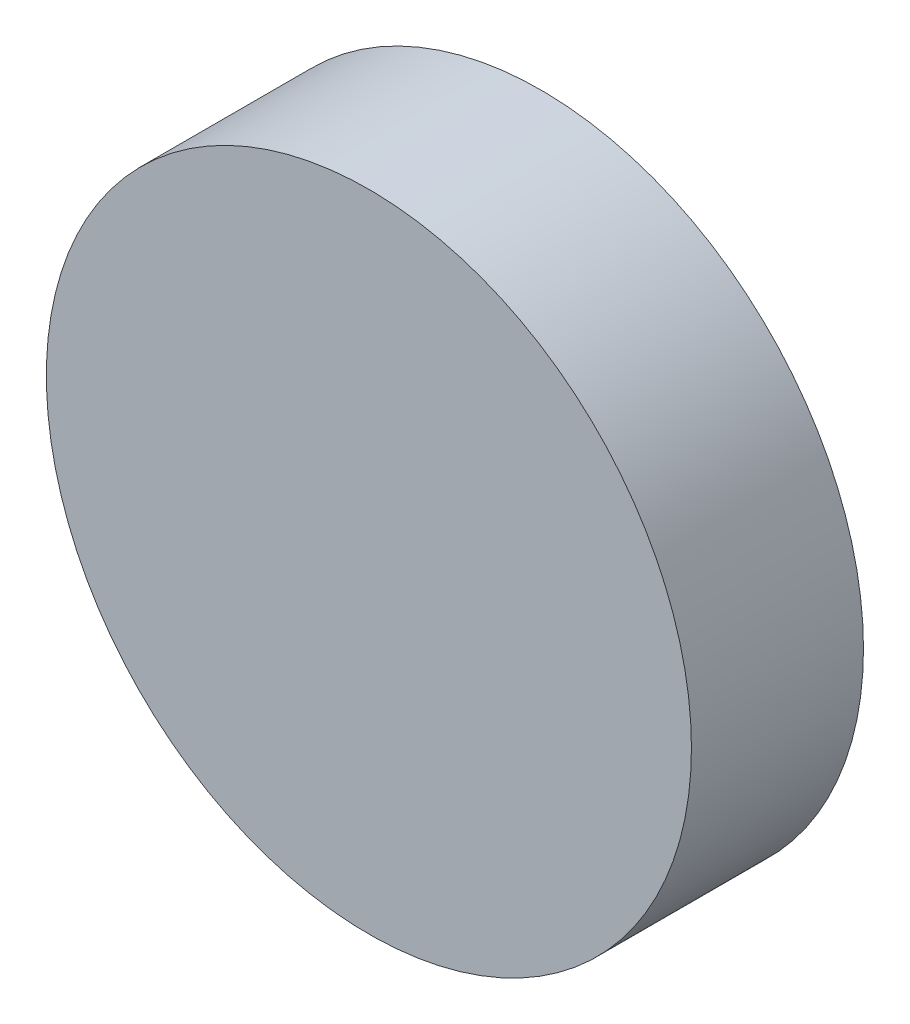
SolidWorks part; units mm, degrees
ref_plane "Front Plane" through (0, 0, 0) normal (0, 0, 1) x (1, 0, 0)
ref_plane "Top Plane" through (0, 0, 0) normal (0, 1, 0) x (1, 0, 0)
ref_plane "Right Plane" through (0, 0, 0) normal (1, 0, 0) x (0, 0, -1)
sketch "Sketch1" plane through (0, 0, 0) normal (0, 0, 1) x (1, 0, 0)
  circle A0 centre (0, 0) radius 37.5
  dimension "D1" = 75
extrude "Boss-Extrude1" add sketch "Sketch1" along normal blind 20
sketch "Sketch2" plane through (0, 0, 0) normal (1, 0, 0) x (0, 0, -1)
  line L0 (0, 0) -> (7, 0)
  line L1 (7, 0) -> (7, 15.9504)
  line L2 (7, 15.9504) -> (0, 37.5)
  line L3 (0, 37.5) -> (0, 0)
  dimension "D1" = 7
